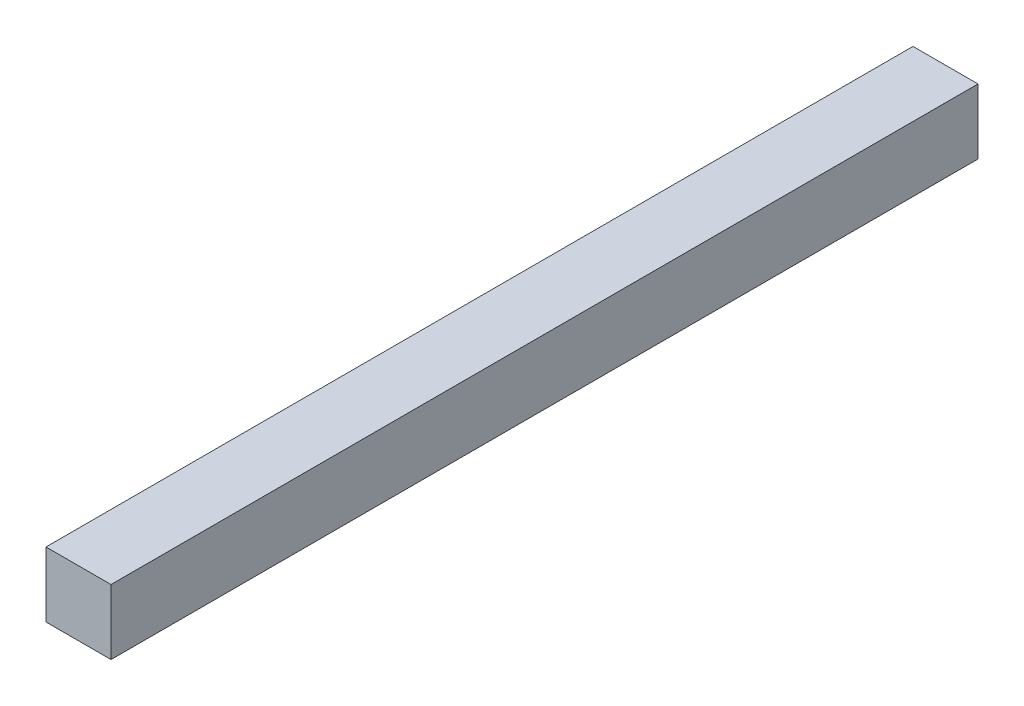
SolidWorks part; units mm, degrees
ref_plane "前视基准面" through (0, 0, 0) normal (0, 0, 1) x (1, 0, 0)
ref_plane "上视基准面" through (0, 0, 0) normal (0, 1, 0) x (1, 0, 0)
ref_plane "右视基准面" through (0, 0, 0) normal (1, 0, 0) x (0, 0, -1)
sketch "草图1" plane through (0, 0, 0) normal (0, 0, 1) x (1, 0, 0)
  line L1 (-15, 15) -> (15, 15)
  line L2 (-15, 15) -> (-15, -15)
  line L3 (-15, -15) -> (15, -15)
  line L4 (15, 15) -> (15, -15)
  line L5 (-15, 15) -> (15, -15) construction
  line L6 (-15, -15) -> (15, 15) construction
  point P0 (0, 0)
  dimension "D1" = 30
  dimension "D2" = 30
extrude "凸台-拉伸1" add sketch "草图1" along normal mid plane 400
